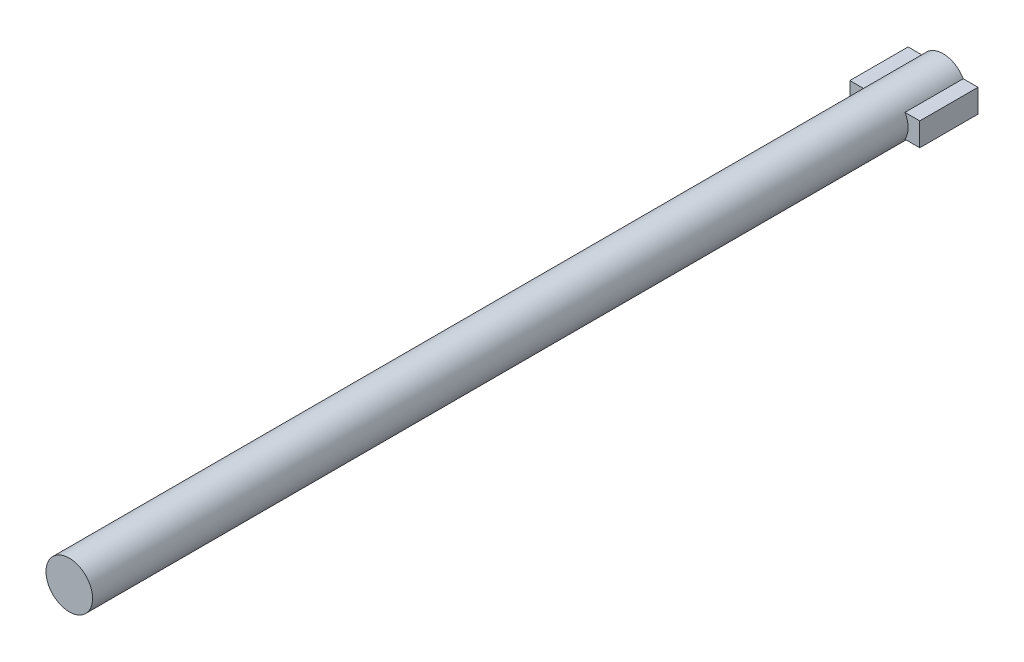
SolidWorks part; units mm, degrees
material "Хромистая нержавеющая сталь"
ref_plane "Спереди" through (0, 0, 0) normal (0, 0, 1) x (1, 0, 0)
ref_plane "Сверху" through (0, 0, 0) normal (0, 1, 0) x (1, 0, 0)
ref_plane "Справа" through (0, 0, 0) normal (1, 0, 0) x (0, 0, -1)
sketch "Эскиз1" plane through (0, 0, 0) normal (0, 0, 1) x (1, 0, 0)
  circle A0 centre (0, 0) radius 4
extrude "Бобышка-Вытянуть1" add sketch "Эскиз1" along normal blind 150
sketch "Эскиз2" plane through (0, 0, 0) normal (0, 0, -1) x (-1, 0, 0)
  line L1 (-6, 2) -> (6, 2)
  line L2 (-6, 2) -> (-6, -2)
  line L3 (-6, -2) -> (6, -2)
  line L4 (6, 2) -> (6, -2)
  dimension "D1" = 4
  dimension "D2" = 12
  dimension "D3" = 2
  dimension "D4" = 6
extrude "Бобышка-Вытянуть2" add sketch "Эскиз2" against normal blind 10
